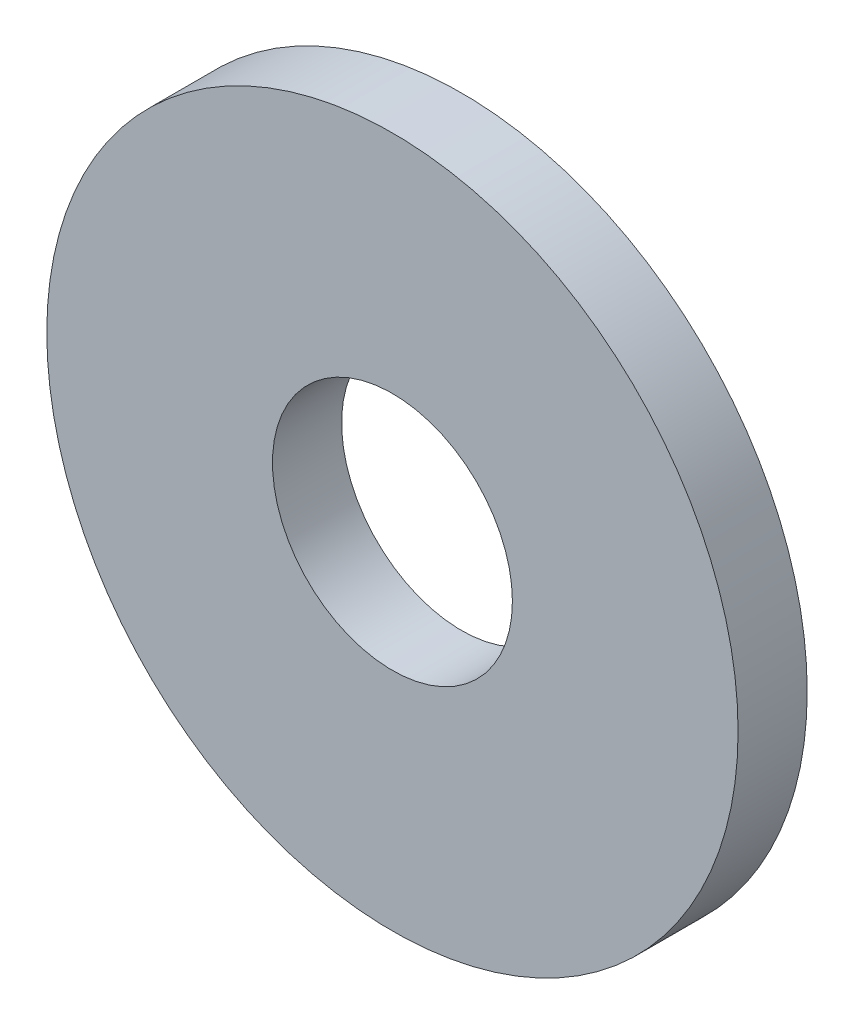
SolidWorks part; units mm, degrees
ref_plane "Front Plane" through (0, 0, 0) normal (0, 0, 1) x (1, 0, 0)
ref_plane "Top Plane" through (0, 0, 0) normal (0, 1, 0) x (1, 0, 0)
ref_plane "Right Plane" through (0, 0, 0) normal (1, 0, 0) x (0, 0, -1)
sketch "Sketch1" plane through (0, 0, 0) normal (0, 0, 1) x (1, 0, 0)
  circle A0 centre (0, 0) radius 8.5
  circle A1 centre (0, 0) radius 2.95
  dimension "D1" = 5.9
  dimension "D2" = 17
extrude "Boss-Extrude1" add sketch "Sketch1" along normal blind 1.7
equation "\"smallPulleyTeeth\"= 15"
equation "\"largePulleyTeeth\"= 40"
equation "\"eighthThick\"= 2.9mm"
equation "\"sixteenthThick\" = 1.7mm"
equation "\"wheelEighthThick\"=3.0mm"
equation "\"quarterThick\"=5.9mm"
equation "\"OD\" = 145mm"
equation "\"puckAngle\" = 60.5deg"
equation "\"puckDiam\" = 76.5mm"
equation "\"axlePress\" = 5.9mm"
equation "\"D1@Sketch1\"=\"axlePress\""
equation "\"D1@Boss-Extrude1\"=\"sixteenthThick\""
